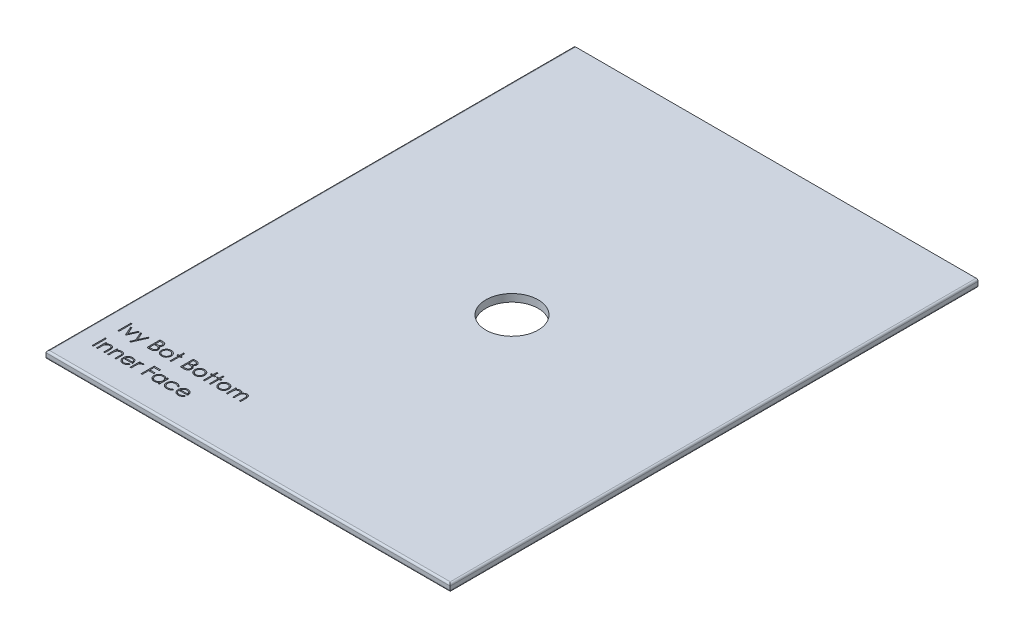
SolidWorks part; units mm, degrees
ref_plane "Front Plane" through (0, 0, 0) normal (0, 0, 1) x (1, 0, 0)
ref_plane "Top Plane" through (0, 0, 0) normal (0, 1, 0) x (1, 0, 0)
ref_plane "Right Plane" through (0, 0, 0) normal (1, 0, 0) x (0, 0, -1)
sketch "Sketch1" plane through (0, 0, 0) normal (0, 1, 0) x (1, 0, 0)
  line L1 (-54, 70.5) -> (54, 70.5)
  line L2 (-54, 70.5) -> (-54, -70.5)
  line L3 (-54, -70.5) -> (54, -70.5)
  line L4 (54, 70.5) -> (54, -70.5)
  point P4 (0, -70.5)
  point P6 (-54, 0)
  dimension "D1" = 108
  dimension "D2" = 141
extrude "Boss-Extrude1" add sketch "Sketch1" along normal blind 2 contours L1 L4 L3 L2
sketch "Sketch6" plane through (0, 2, 0) normal (0, 1, 0) x (1, 0, 0)
  circle A0 centre (0, 0) radius 7
  dimension "D1" = 14
extrude "Cut-Extrude1" cut sketch "Sketch6" against normal through all contours A0
fillet "Fillet1" radius 0.5 7 edges at (-54, 0, 0) (0, 0, -70.5) (0, 0, 70.5) (54, 0, 0) (54, 2, 0) (-54, 2, 0) (0, 2, 70.5)
sketch "Sketch9" plane through (0, 2, 0) normal (0, 1, 0) x (1, 0, 0)
  text T0 "Ivy Bot Bottom\r\nInner Face"
extrude "Cut-Extrude4" cut sketch "Sketch9" against normal blind 1
sketch "Sketch10" plane through (0, 0, 0) normal (0, -1, 0) x (1, 0, 0)
  line L0 (-12.9733, 25) -> (12.9733, 25) construction
  line L1 (-12.9733, -25) -> (12.9733, -25) construction
  text T0 "3               1"
  text T1 " 2               4"
  point P8 (0, 25)
  point P12 (0, -25)
  dimension "D1" = 25
  dimension "D2" = 25
extrude "Cut-Extrude5" cut sketch "Sketch10" against normal blind 1
